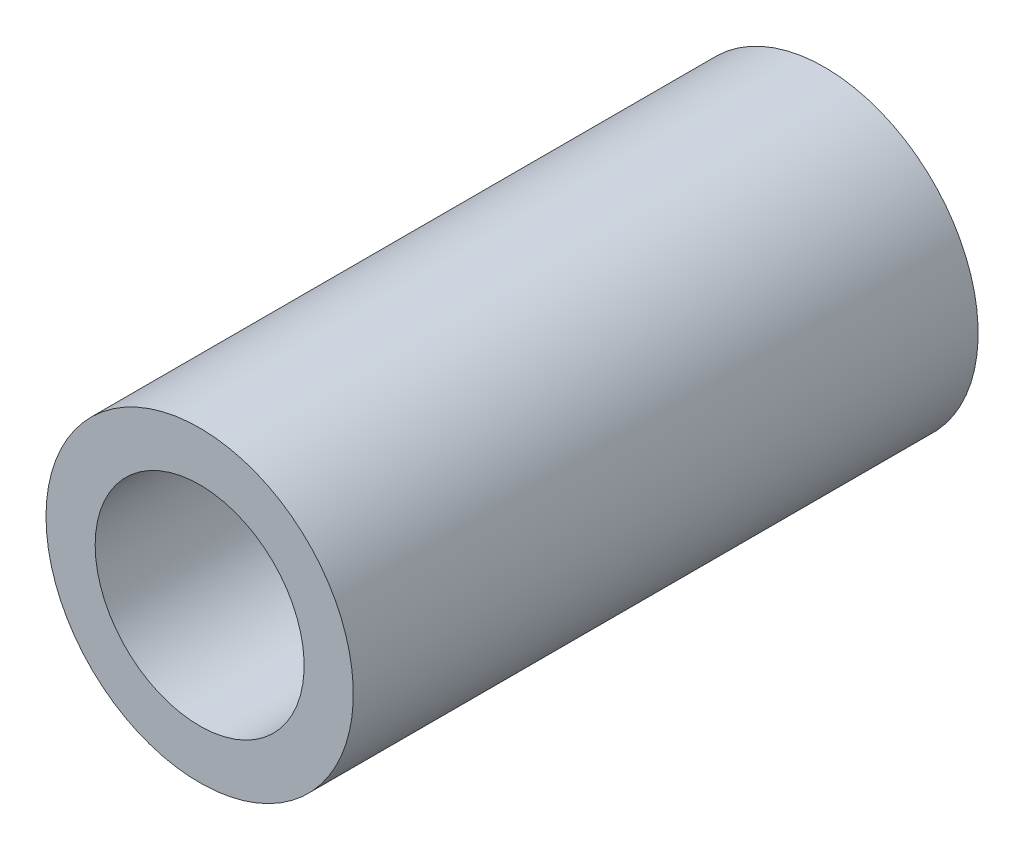
SolidWorks part; units mm, degrees
ref_plane "前视基准面" through (0, 0, 0) normal (0, 0, 1) x (1, 0, 0)
ref_plane "上视基准面" through (0, 0, 0) normal (0, 1, 0) x (1, 0, 0)
ref_plane "右视基准面" through (0, 0, 0) normal (1, 0, 0) x (0, 0, -1)
sketch "草图1" plane through (0, 0, 0) normal (0, 0, 1) x (1, 0, 0)
  circle A0 centre (0, 0) radius 5.1
  circle A1 centre (0, 0) radius 7.5
  dimension "D1" = 10.2
  dimension "D2" = 15
extrude "凸台-拉伸1" add sketch "草图1" along normal blind 30.5
